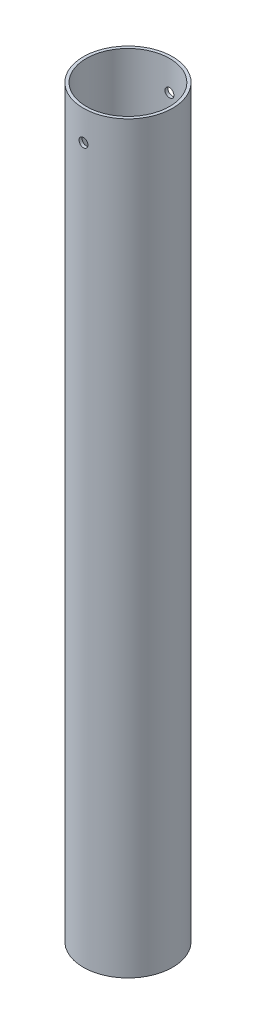
SolidWorks part; units mm, degrees
material "A-Glass Fiber"
ref_plane "Front Plane" through (0, 0, 0) normal (0, 0, 1) x (1, 0, 0)
ref_plane "Top Plane" through (0, 0, 0) normal (0, 1, 0) x (1, 0, 0)
ref_plane "Right Plane" through (0, 0, 0) normal (1, 0, 0) x (0, 0, -1)
sketch "Sketch1" plane through (0, 0, 0) normal (0, 1, 0) x (1, 0, 0)
  circle A0 centre (0, 0) radius 15
  circle A1 centre (0, 0) radius 14
  dimension "D1" = 30
  dimension "D2" = 28
extrude "Boss-Extrude1" add sketch "Sketch1" along normal blind 250
ref_plane "Plane1" through (0, 0, 15) normal (0, 0, 1) x (1, 0, 0)
sketch "Sketch2" plane through (0, 0, 15) normal (0, 0, 1) x (1, 0, 0)
  line L0 (15, 250) -> (-15, 250) construction
  circle A0 centre (0, 240) radius 1.5
  dimension "D1" = 3
  dimension "D2" = 10
extrude "Cut-Extrude1" cut sketch "Sketch2" against normal through all both
